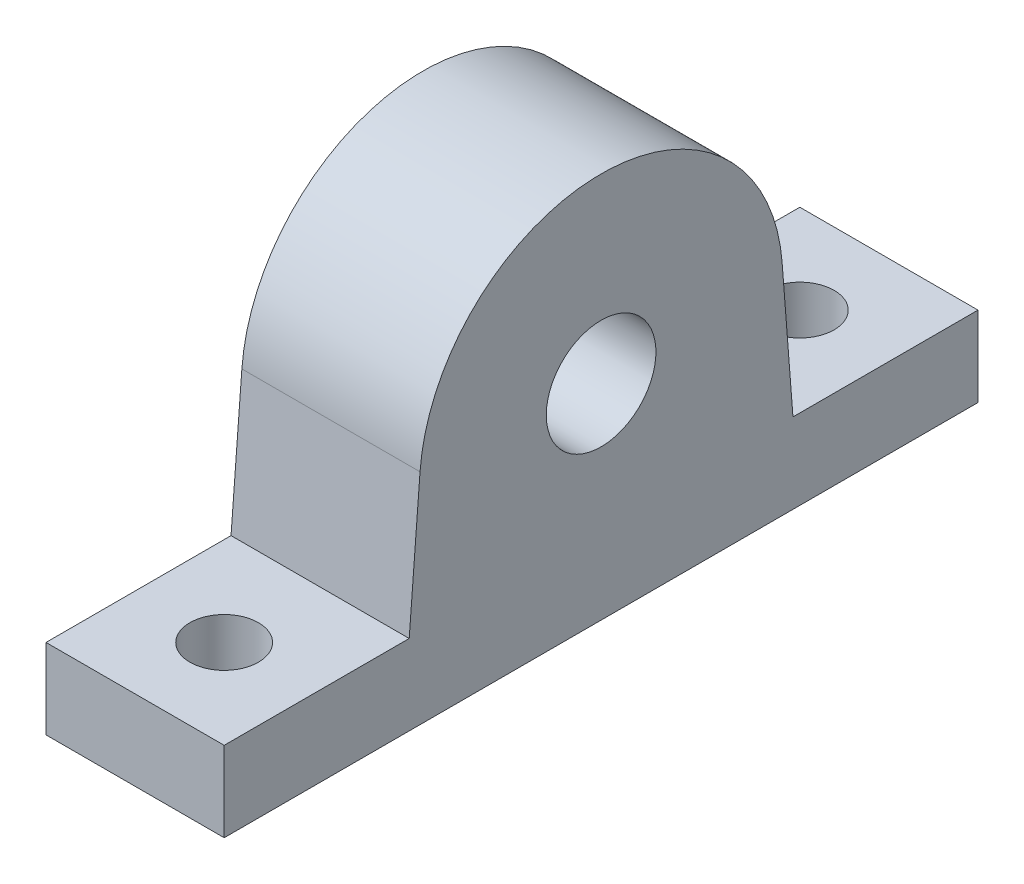
SolidWorks part; units mm, degrees
ref_plane "Front Plane" through (0, 0, 0) normal (0, 0, 1) x (1, 0, 0)
ref_plane "Top Plane" through (0, 0, 0) normal (0, 1, 0) x (1, 0, 0)
ref_plane "Right Plane" through (0, 0, 0) normal (1, 0, 0) x (0, 0, -1)
sketch "Sketch1" plane through (0, 0, 0) normal (1, 0, 0) x (0, 0, -1)
  line L0 (27.5, -14.95) -> (-27.5, -14.95)
  line L1 (-27.5, -14.95) -> (-27.5, -9.1078)
  line L2 (-27.5, -9.1078) -> (-14, -9.1078)
  line L3 (-14, -9.1078) -> (-13.2099, 1.0295)
  line L4 (0, 13.25) -> (0, -14.95) construction
  line L5 (14, -9.1078) -> (13.2099, 1.0295)
  line L6 (27.5, -9.1078) -> (14, -9.1078)
  line L7 (27.5, -14.95) -> (27.5, -9.1078)
  arc A0 (13.2099, 1.0295) -> (-13.2099, 1.0295) centre (0, 0) ccw
  circle A1 centre (0, 0) radius 4
  point P5 (0, 13.25)
  dimension "D1" = 26.5
  dimension "D5" = 8
  dimension "D2" = 28.2
  dimension "D3" = 27.5
  dimension "D4" = 14
extrude "Boss-Extrude1" add sketch "Sketch1" along normal blind 13
sketch "Sketch2" plane through (0, -9.1078, 0) normal (0, 1, 0) x (1, 0, 0)
  line L0 (6.5, 27.5) -> (6.5, -27.5) construction
  line L1 (13, 27.5) -> (0, 27.5) construction
  line L2 (13, -27.5) -> (0, -27.5) construction
  line L3 (0, 0) -> (13, 0) construction
  line L4 (13, -13.2099) -> (13, 13.2099) construction
  circle A0 centre (6.5, 21) radius 2.5
  circle A1 centre (6.5, -21) radius 2.5
  dimension "D1" = 5
  dimension "D2" = 21
extrude "Cut-Extrude1" cut sketch "Sketch2" against normal through all both and the other way through all
